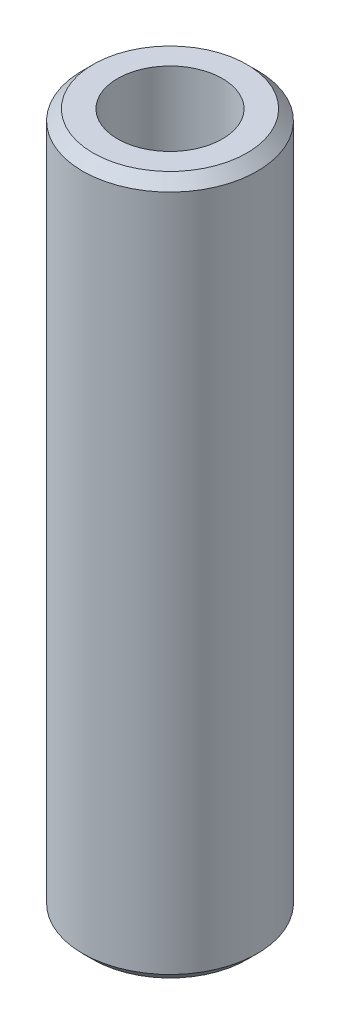
SolidWorks part; units mm, degrees
ref_plane "前视基准面" through (0, 0, 0) normal (0, 0, 1) x (1, 0, 0)
ref_plane "上视基准面" through (0, 0, 0) normal (0, 1, 0) x (1, 0, 0)
ref_plane "右视基准面" through (0, 0, 0) normal (1, 0, 0) x (0, 0, -1)
sketch "草图1" plane through (0, 0, 0) normal (0, 1, 0) x (1, 0, 0)
  circle A0 centre (0, 0) radius 2.5
  circle A1 centre (0, 0) radius 1.5
  dimension "D1" = 5
  dimension "D2" = 3
extrude "凸台-拉伸1" add sketch "草图1" along normal blind 20
chamfer "倒角1" distance 0.3 angle 45 2 edges at (0, 0, 2.5) (0, 20, 2.5)
